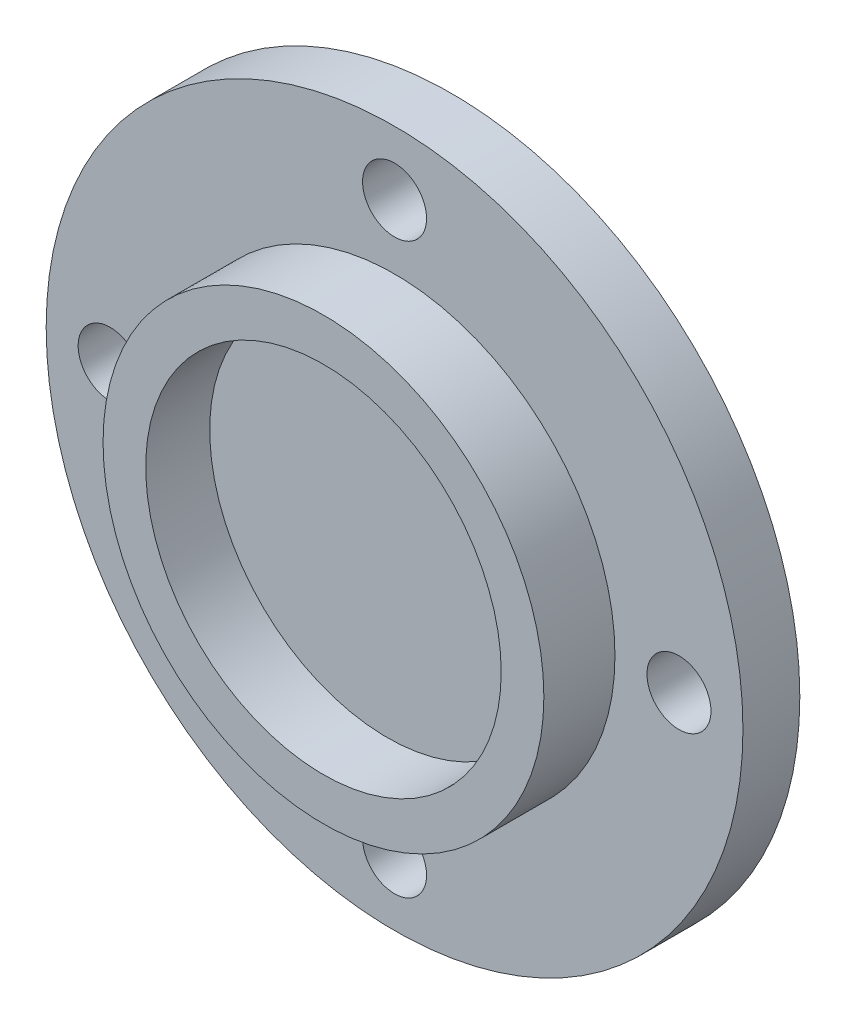
SolidWorks part; units mm, degrees
ref_plane "前视基准面" through (0, 0, 0) normal (0, 0, 1) x (1, 0, 0)
ref_plane "上视基准面" through (0, 0, 0) normal (0, 1, 0) x (1, 0, 0)
ref_plane "右视基准面" through (0, 0, 0) normal (1, 0, 0) x (0, 0, -1)
sketch "草图1" plane through (0, 0, 0) normal (0, 0, 1) x (1, 0, 0)
  circle A0 centre (0, 0) radius 49
extrude "凸台-拉伸1" add sketch "草图1" along normal blind 8
sketch "草图2" plane through (0, 0, 8) normal (0, 0, 1) x (1, 0, 0)
  circle A0 centre (0, 0) radius 31
extrude "凸台-拉伸2" add sketch "草图2" along normal blind 10
sketch "草图3" plane through (0, 0, 18) normal (0, 0, 1) x (1, 0, 0)
  circle A0 centre (0, 0) radius 25
extrude "切除-拉伸1" cut sketch "草图3" against normal blind 9
sketch "草图4" plane through (0, 0, 8) normal (0, 0, 1) x (1, 0, 0)
  circle A0 centre (0, 40) radius 4.5
  circle A1 centre (40, 0) radius 4.5
  circle A2 centre (0, -40) radius 4.5
  circle A3 centre (-40, 0) radius 4.5
extrude "切除-拉伸2" cut sketch "草图4" against normal blind 49
